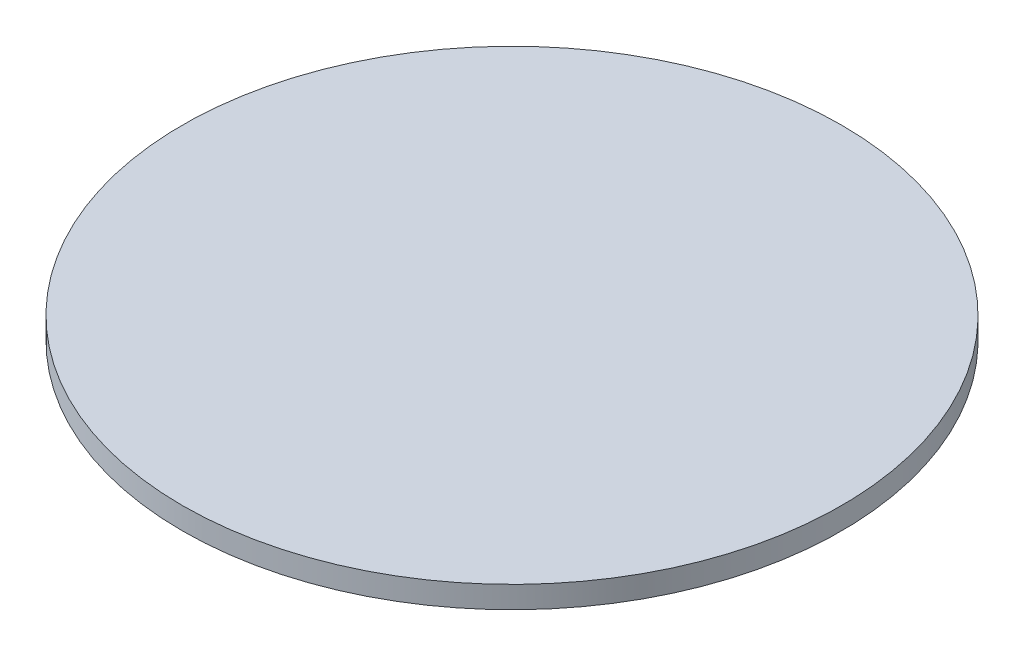
SolidWorks part; units mm, degrees
ref_plane "Alzado" through (0, 0, 0) normal (0, 0, 1) x (1, 0, 0)
ref_plane "Planta" through (0, 0, 0) normal (0, 1, 0) x (1, 0, 0)
ref_plane "Vista lateral" through (0, 0, 0) normal (1, 0, 0) x (0, 0, -1)
sketch "Croquis1" plane through (0, 0, 0) normal (0, 1, 0) x (1, 0, 0)
  circle A0 centre (0, 0) radius 15
  dimension "D1" = 30
extrude "Saliente-Extruir1" add sketch "Croquis1" along normal blind 1
